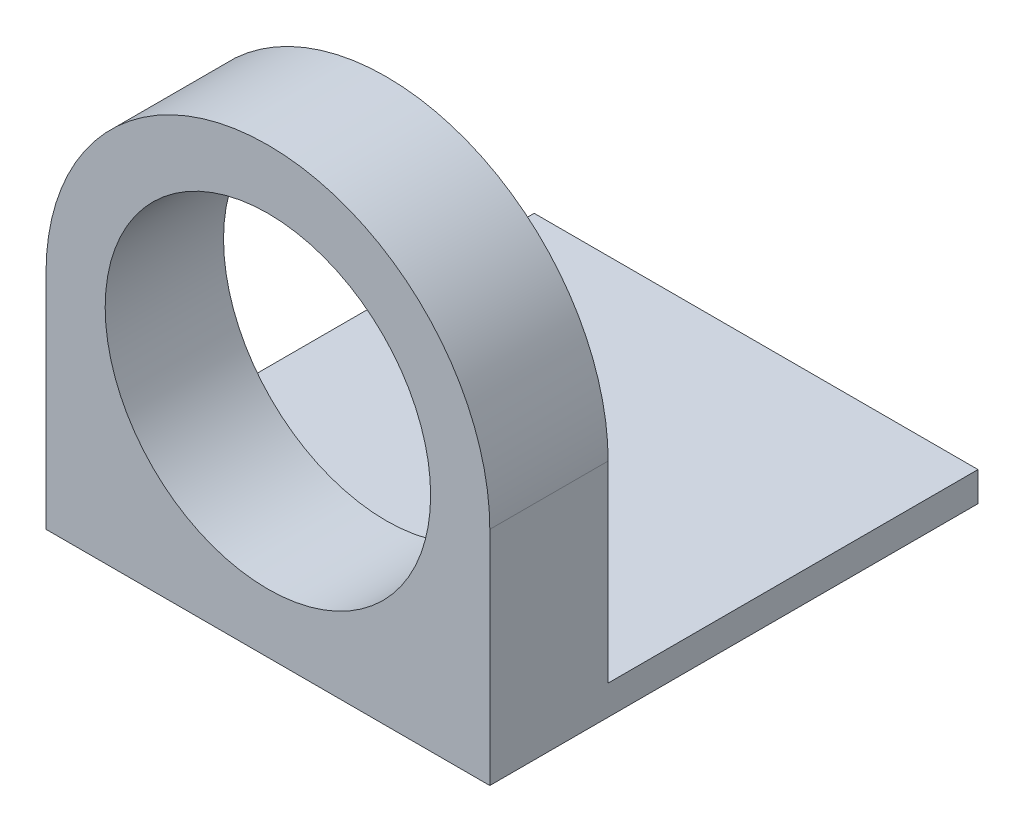
SolidWorks part; units mm, degrees
ref_plane "Front Plane" through (0, 0, 0) normal (0, 0, 1) x (1, 0, 0)
ref_plane "Top Plane" through (0, 0, 0) normal (0, 1, 0) x (1, 0, 0)
ref_plane "Right Plane" through (0, 0, 0) normal (1, 0, 0) x (0, 0, -1)
sketch "Sketch2" plane through (0, 0, 0) normal (0, 0, 1) x (1, 0, 0)
  line L0 (0, -15) -> (-15, -15)
  line L1 (-15, 0) -> (-15, -15)
  line L2 (0, -15) -> (15, -15)
  line L3 (15, 0) -> (15, -15)
  circle A0 centre (0, 0) radius 11
  arc A1 (15, 0) -> (-15, 0) centre (0, 0) ccw
  dimension "D1" = 22
  dimension "D2" = 30
extrude "Boss-Extrude1" add sketch "Sketch2" along normal blind 8
sketch "Sketch3" plane through (0, 0, 0) normal (0, 0, -1) x (-1, 0, 0)
  line L0 (15, 0) -> (15, -15) construction
  line L1 (-15, -15) -> (15, -15)
  line L2 (-15, -15) -> (-15, -13)
  line L3 (-15, -13) -> (15, -13)
  line L4 (15, -15) -> (15, -13)
  dimension "D1" = 2
extrude "Boss-Extrude2" add sketch "Sketch3" along normal blind 25
